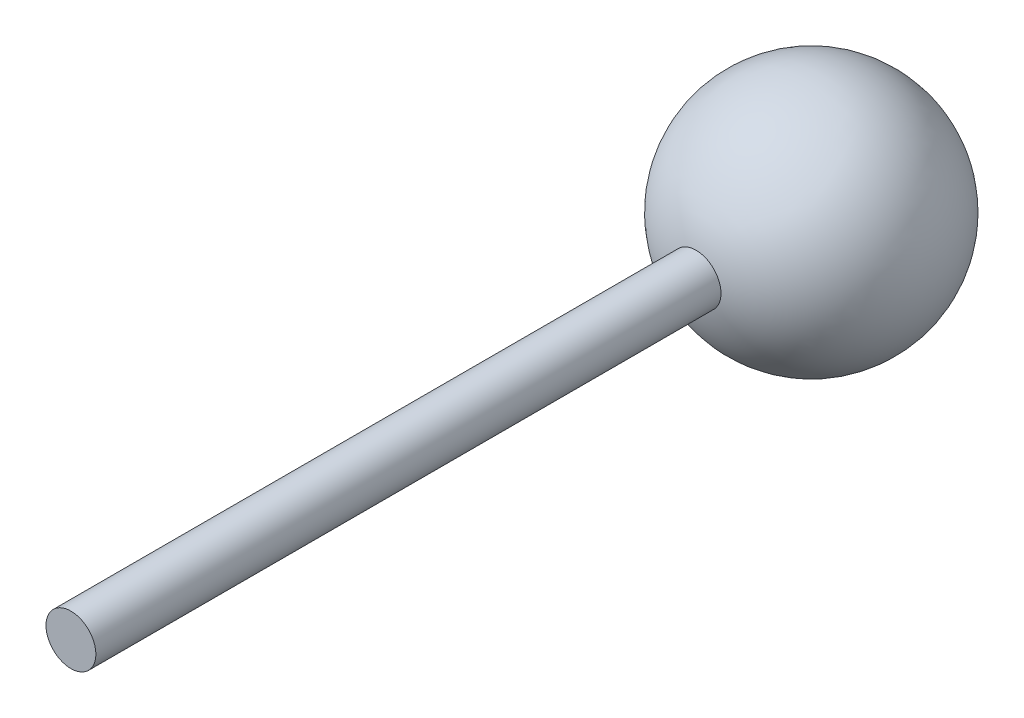
SolidWorks part; units mm, degrees
ref_plane "Front Plane" through (0, 0, 0) normal (0, 0, 1) x (1, 0, 0)
ref_plane "Top Plane" through (0, 0, 0) normal (0, 1, 0) x (1, 0, 0)
ref_plane "Right Plane" through (0, 0, 0) normal (1, 0, 0) x (0, 0, -1)
sketch "Sketch2" plane through (0, 0, 0) normal (0, 1, 0) x (1, 0, 0)
  line L0 (0, 28.3771) -> (0, -28.1791)
  line L1 (0, -28.1791) -> (0, -178.1791)
  line L2 (0, -178.1791) -> (-6, -178.1791)
  line L3 (-6, -178.1791) -> (-6, -27.7356)
  arc A0 (0, 28.3771) -> (-6, -27.7356) centre (0, 0) ccw
  point P1 (0, 0)
  point P8 (0, 0)
  point P9 (0, -178.0696)
  dimension "D1" = 6
  dimension "D4" = 28.3771
  dimension "D3" = 150
revolve "Revolve2" add sketch "Sketch2" angle 360 about L0
